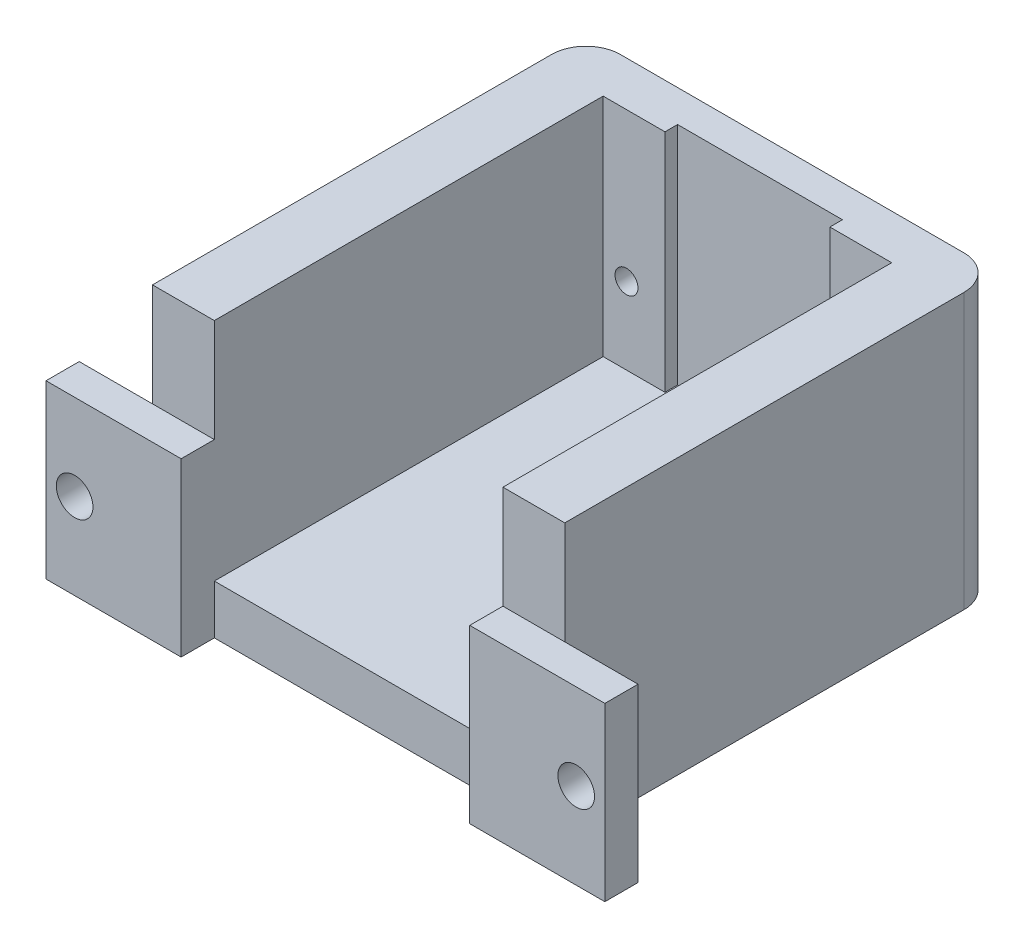
SolidWorks part; units mm, degrees
ref_plane "前视基准面" through (0, 0, 0) normal (0, 0, 1) x (1, 0, 0)
ref_plane "上视基准面" through (0, 0, 0) normal (0, 1, 0) x (1, 0, 0)
ref_plane "右视基准面" through (0, 0, 0) normal (1, 0, 0) x (0, 0, -1)
other "Configuration Table"
sketch "草图3" plane through (0, 0, 0) normal (0, 1, 0) x (1, 0, 0)
  line L1 (-18, -25) -> (18, -25)
  line L2 (-18, -25) -> (-18, 25)
  line L3 (-18, 25) -> (18, 25)
  line L4 (18, -25) -> (18, 25)
  line L5 (-18, -25) -> (18, 25) construction
  line L6 (-18, 25) -> (18, -25) construction
  point P0 (0, 0)
  dimension "D1" = 36
  dimension "D2" = 50
extrude "凸台-拉伸1" add sketch "草图3" along normal blind 24
sketch "草图4" plane through (0, 24, 0) normal (0, 1, 0) x (1, 0, 0)
  line L1 (-12.4, -15.9) -> (12.4, -15.9)
  line L2 (-12.4, -15.9) -> (-12.4, 15.9)
  line L3 (-12.4, 15.9) -> (12.4, 15.9)
  line L4 (12.4, -15.9) -> (12.4, 15.9)
  line L5 (-12.4, -15.9) -> (12.4, 15.9) construction
  line L6 (-12.4, 15.9) -> (12.4, -15.9) construction
  point P0 (0, 0)
  dimension "D1" = 24.8
  dimension "D2" = 31.8
extrude "切除-拉伸1" cut sketch "草图4" against normal blind 19.7
sketch "草图5" plane through (0, 24, 0) normal (0, 1, 0) x (1, 0, 0)
  line L0 (12.4, 15.9) -> (-12.4, 15.9) construction
  line L1 (-7, 14.8) -> (7, 14.8)
  line L2 (-7, 14.8) -> (-7, 17)
  line L3 (-7, 17) -> (7, 17)
  line L4 (7, 14.8) -> (7, 17)
  line L5 (-7, 14.8) -> (7, 17) construction
  line L6 (-7, 17) -> (7, 14.8) construction
  point P0 (0, 15.9)
  dimension "D1" = 14
  dimension "D2" = 2.2
extrude "切除-拉伸3" cut sketch "草图5" against normal blind 19.7 contours L3 L4 L1 L2
sketch "草图6" plane through (0, 24, 0) normal (0, 1, 0) x (1, 0, 0)
  line L0 (-12.4, -15.9) -> (12.4, -15.9) construction
  line L1 (-9.25, -17.8) -> (9.25, -17.8)
  line L2 (-9.25, -17.8) -> (-9.25, -14)
  line L3 (-9.25, -14) -> (9.25, -14)
  line L4 (9.25, -17.8) -> (9.25, -14)
  line L5 (-9.25, -17.8) -> (9.25, -14) construction
  line L6 (-9.25, -14) -> (9.25, -17.8) construction
  point P0 (0, -15.9)
  dimension "D1" = 18.5
  dimension "D2" = 3.8
extrude "切除-拉伸4" cut sketch "草图6" against normal blind 14.7
sketch "草图7" plane through (0, 24, 0) normal (0, 1, 0) x (1, 0, 0)
  line L0 (-18, -25) -> (18, -25) construction
  line L1 (-12.4, -37.1402) -> (12.4, -37.1402)
  line L2 (-12.4, -37.1402) -> (-12.4, -12.8598)
  line L3 (-12.4, -12.8598) -> (12.4, -12.8598)
  line L4 (12.4, -37.1402) -> (12.4, -12.8598)
  line L5 (-12.4, -37.1402) -> (12.4, -12.8598) construction
  line L6 (-12.4, -12.8598) -> (12.4, -37.1402) construction
  point P0 (0, -25)
  dimension "D1" = 24.8
extrude "切除-拉伸5" cut sketch "草图7" against normal blind 2
sketch "草图8" plane through (0, 0, 25) normal (0, 0, 1) x (1, 0, 0)
  line L0 (18, 24) -> (18, 0) construction
  line L1 (-18, 0) -> (18, 0) construction
  line L2 (-18, 24) -> (-18, 0) construction
  circle A0 centre (10.65, 7.2) radius 2
  circle A1 centre (-10.65, 7.2) radius 2
  dimension "D1" = 7.35
  dimension "D3" = 7.35
  dimension "D2" = 7.2
  dimension "D4" = 7.2
extrude "切除-拉伸6" cut sketch "草图8" against normal blind 6.4
sketch "草图9" plane through (0, 0, 18.6) normal (0, 0, 1) x (1, 0, 0)
  circle A0 centre (10.65, 7.2) radius 1
  circle A1 centre (-10.65, 7.2) radius 1
extrude "切除-拉伸7" cut sketch "草图9" against normal blind 6.4
sketch "草图10" plane through (0, 0, -25) normal (0, 0, -1) x (-1, 0, 0)
  line L0 (-18, 24) -> (-18, 0) construction
  line L1 (-18, 0) -> (18, 0) construction
  line L2 (18, 24) -> (18, 0) construction
  circle A0 centre (-10.565, 11) radius 2
  circle A1 centre (10.56, 11) radius 2
  dimension "D1" = 7.435
  dimension "D3" = 7.44
  dimension "D2" = 11
  dimension "D4" = 11
extrude "切除-拉伸8" cut sketch "草图10" against normal blind 7.4
sketch "草图11" plane through (0, 0, -17.6) normal (0, 0, -1) x (-1, 0, 0)
  circle A0 centre (10.56, 11) radius 1
  circle A1 centre (-10.565, 11) radius 1
extrude "切除-拉伸9" cut sketch "草图11" against normal blind 7.4
sketch "草图14" plane through (0, 0, 25) normal (0, 0, 1) x (1, 0, 0)
  line L1 (-26.5003, 33.3651) -> (21.1929, 33.3651)
  line L2 (-26.5003, 33.3651) -> (-26.5003, -8.5784)
  line L3 (-26.5003, -8.5784) -> (21.1929, -8.5784)
  line L4 (21.1929, 33.3651) -> (21.1929, -8.5784)
extrude "切除-拉伸12" cut sketch "草图14" against normal blind 4
sketch "草图16" plane through (0, 0, -25) normal (0, 0, -1) x (-1, 0, 0)
  line L1 (-33.7246, 32.2994) -> (35.4423, 32.2994)
  line L2 (-33.7246, 32.2994) -> (-33.7246, -7.1228)
  line L3 (-33.7246, -7.1228) -> (35.4423, -7.1228)
  line L4 (35.4423, 32.2994) -> (35.4423, -7.1228)
extrude "切除-拉伸13" cut sketch "草图16" against normal blind 5
sketch "草图18" plane through (0, 24, 0) normal (0, 1, 0) x (1, 0, 0)
  line L113 (-12.6, -16.1) -> (12.6, -16.1)
  line L114 (-12.6, 16.1) -> (-12.6, -16.1)
  line L115 (-7.2, 16.1) -> (-12.6, 16.1)
  line L116 (-7.2, 17.2) -> (-7.2, 16.1)
  line L117 (7.2, 17.2) -> (-7.2, 17.2)
  line L118 (7.2, 16.1) -> (7.2, 17.2)
  line L119 (12.6, 16.1) -> (7.2, 16.1)
  line L120 (12.6, -16.1) -> (12.6, 16.1)
  line L121 (-12.6, -16.1) -> (12.6, -16.1)
  line L122 (-12.6, 16.1) -> (-12.6, -16.1)
  line L123 (-7.2, 16.1) -> (-12.6, 16.1)
  line L124 (-7.2, 17.2) -> (-7.2, 16.1)
  line L125 (7.2, 17.2) -> (-7.2, 17.2)
  line L126 (7.2, 16.1) -> (7.2, 17.2)
  line L127 (12.6, 16.1) -> (7.2, 16.1)
  line L128 (12.6, -16.1) -> (12.6, 16.1)
  dimension "D1" = 0.2
extrude "切除-拉伸17" cut sketch "草图18" against normal blind 19.7
sketch "草图19" plane through (0, 22, 0) normal (0, 1, 0) x (1, 0, 0)
  line L14 (9.3, -17.85) -> (9.3, -16.05)
  line L15 (-9.3, -16.05) -> (-9.3, -17.85)
  line L16 (-9.3, -17.85) -> (9.3, -17.85)
  line L17 (9.3, -16.05) -> (-9.3, -16.05)
  line L18 (9.3, -17.85) -> (9.3, -16.05)
  line L19 (-9.3, -16.05) -> (-9.3, -17.85)
  line L20 (-9.3, -17.85) -> (9.3, -17.85)
  line L21 (9.3, -16.05) -> (-9.3, -16.05)
  dimension "D1" = 0.05
extrude "切除-拉伸18" cut sketch "草图19" against normal blind 12.7
sketch "草图20" plane through (0, 0, 21) normal (0, 0, 1) x (1, 0, 0)
  line L1 (-28.6025, 34.8849) -> (38.0946, 34.8849)
  line L2 (-28.6025, 34.8849) -> (-28.6025, -28.1996)
  line L3 (-28.6025, -28.1996) -> (38.0946, -28.1996)
  line L4 (38.0946, 34.8849) -> (38.0946, -28.1996)
extrude "切除-拉伸19" cut sketch "草图20" against normal up to surface (3.15 mm away) up to face at (0, 15.65, 17.85)
sketch "草图21" plane through (0, 0, 17.85) normal (0, 0, 1) x (1, 0, 0)
  line L0 (-12.6, 4.3) -> (12.6, 4.3) construction
  line L1 (-12.4, 22) -> (12.4, 22)
  line L2 (-12.4, 22) -> (-12.4, 4.3)
  line L3 (-12.4, 4.3) -> (12.4, 4.3)
  line L4 (12.4, 22) -> (12.4, 4.3)
  dimension "D1" = 0
  dimension "D2" = 0
extrude "切除-拉伸20" cut sketch "草图21" against normal blind 10
sketch "草图22" plane through (0, 0, 17.85) normal (0, 0, 1) x (1, 0, 0)
  line L1 (12.4, 15) -> (24.4, 15)
  line L2 (12.4, 15) -> (12.4, 0)
  line L3 (12.4, 0) -> (24.4, 0)
  line L4 (24.4, 15) -> (24.4, 0)
  line L5 (12.4, 24) -> (12.4, 4.3) construction
  circle A0 centre (21.9, 7.5) radius 1.6
  dimension "D4" = 7.5
  dimension "D1" = 12
  dimension "D2" = 15
  dimension "D3" = 0
  dimension "D5" = 2.5
extrude "凸台-拉伸2" add sketch "草图22" along normal blind 2.9
mirror "镜向1" about plane through (0, 0, 0) normal (1, 0, 0) of "凸台-拉伸2"
sketch "草图23" plane through (0, 24, 0) normal (0, 1, 0) x (1, 0, 0)
  line L0 (12.6, -16.1) -> (12.6, 16.1) construction
  line L1 (-12.6, 16.1) -> (12.6, 16.1)
  line L2 (-12.6, 16.1) -> (-12.6, -23.1252)
  line L3 (-12.6, -23.1252) -> (12.6, -23.1252)
  line L4 (12.6, 16.1) -> (12.6, -23.1252)
  dimension "D1" = 0
extrude "切除-拉伸22" cut sketch "草图23" against normal up to surface (19.7 mm away) up to face at (0, 4.3, 0.1083)
sketch "草图24" plane through (0, 4.3, 0) normal (0, 1, 0) x (1, 0, 0)
  line L0 (-12.6, 16.1) -> (-12.6, -20.75) construction
  line L1 (-12.6, -17.85) -> (12.6, -17.85)
  line L2 (-12.6, -17.85) -> (-12.6, -20.75)
  line L3 (-12.6, -20.75) -> (12.6, -20.75)
  line L4 (12.6, -17.85) -> (12.6, -20.75)
  line L5 (-12.4, -17.85) -> (12.4, -17.85) construction
  dimension "D1" = 0
extrude "切除-拉伸23" cut sketch "草图24" against normal up to surface (4.3 mm away) up to face at (0, 0, 12.5083)
fillet "圆角1" radius 3 2 edges at (18, 12, -20) (-18, 12, -20)
